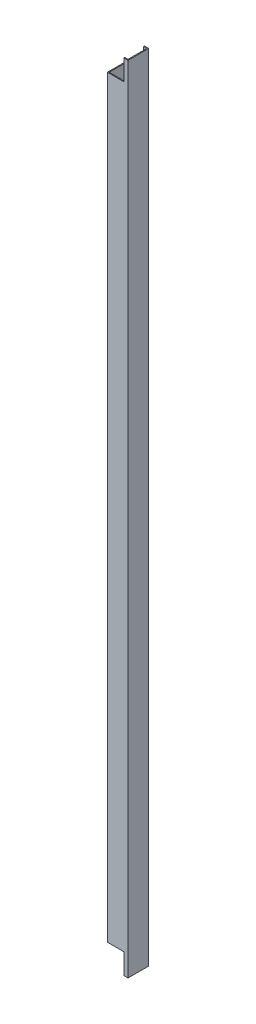
SolidWorks part; units mm, degrees
ref_plane "Front Plane" through (0, 0, 0) normal (0, 0, 1) x (1, 0, 0)
ref_plane "Top Plane" through (0, 0, 0) normal (0, 1, 0) x (1, 0, 0)
ref_plane "Right Plane" through (0, 0, 0) normal (1, 0, 0) x (0, 0, -1)
sketch "Sketch1" plane through (0, 0, 0) normal (0, 1, 0) x (1, 0, 0)
  line L0 (0, 0) -> (0, 50)
  line L1 (0, 50) -> (50, 50)
  line L2 (50, 50) -> (50, 0)
  line L3 (50, 0) -> (0, 0)
  line L4 (2.2, 47.8) -> (47.8, 47.8)
  line L5 (47.8, 47.8) -> (47.8, 2.2)
  line L6 (47.8, 2.2) -> (2.2, 2.2)
  line L7 (2.2, 2.2) -> (2.2, 47.8)
  dimension "D1" = 50
  dimension "D2" = 50
  dimension "D3" = 2.2
extrude "Boss-Extrude1" add sketch "Sketch1" along normal blind 1923
sketch "Sketch2" plane through (0, 0, 0) normal (0, 0, 1) x (1, 0, 0)
  line L0 (0, 0) -> (0, 50)
  line L1 (0, 1923) -> (0, 0) construction
  line L2 (0, 50) -> (40, 50)
  line L3 (40, 50) -> (40, 0)
  line L5 (40, 0) -> (0, 0)
  line L6 (0, 1923) -> (40, 1923)
  line L7 (0, 1923) -> (50, 1923) construction
  line L8 (40, 1923) -> (40, 1873)
  line L9 (40, 1873) -> (0, 1873)
  line L10 (0, 1873) -> (0, 1923)
  dimension "D1" = 50
  dimension "D2" = 40
  dimension "D3" = 50
  dimension "40" = 40
extrude "Cut-Extrude2" cut sketch "Sketch2" against normal blind 50
equation "\"SquareTube_length\"=1923.0"
equation "\"D1@Boss-Extrude1\"=\"SquareTube_length\""
equation "\"SquareTube_inFront1_cutDepth50_R\"=0.5"
equation "\"D1@Sketch2\" = \"SquareTube_inFront5_cutDepth50_R\""
equation "\"SquareTube_inFront1_cutDepth50_L\"=0.5"
equation "\"D3@Sketch2\"= \"SquareTube_inFront5_cutDepth50_L\""
equation "\"CarBeamWidth\"=700.0"
equation "\"MetalSheet_3mm_length\"=5030.0"
equation "\"MetalSheet_3mm_width\"=1923.0"
equation "\"MetalSheet_3mm_FloorCut_L_length\"=1764.0"
equation "\"MetalSheet_3mm_FloorCut_L_disdance\"=1665.0"
equation "\"MetalSheet_3mm_FloorCut_R_length\"=1764.0"
equation "\"MetalSheet_3mm_FloorCut_R_disdance\"=1665.0"
equation "\"indoorHeight\"=1940.0"
equation "\"x\"=66.0"
equation "\"da\"=62.0"
equation "\"SquareTube_wheel_length\"= 750"
equation "\"channelSteel_length\"=5030.0"
equation "\"SquareTube_inFront2_cutDepth50_R\"=0.5"
equation "\"SquareTube_inFront2_cutDepth50_L\"=0.5"
equation "\"SquareTube_inFront3_cutDepth50_R\"=0.5"
equation "\"SquareTube_inFront3_cutDepth50_L\"=0.5"
equation "\"SquareTube_inFront4_cutDepth50_R\"=0.5"
equation "\"SquareTube_inFront4_cutDepth50_L\"=0.5"
equation "\"SquareTube_inFront5_cutDepth50_R\"=50"
equation "\"SquareTube_inFront5_cutDepth50_L\"=50"
equation "\"SquareTube_inFront6_cutDepth50_R\"=50"
equation "\"SquareTube_inFront6_cutDepth50_L\"=50"
equation "\"SquareTube_inFront7_cutDepth50_R\"=50"
equation "\"SquareTube_inFront7_cutDepth50_L\"=50"
equation "\"SquareTube_inFront8_cutDepth50_R\"=50"
equation "\"SquareTube_inFront8_cutDepth50_L\"=50"
equation "\"SquareTube_inFront9_cutDepth50_R\"=50"
equation "\"SquareTube_inFront9_cutDepth50_L\"=50"
equation "\"SquareTube_inFront10_cutDepth50_R\"=50"
equation "\"SquareTube_inFront10_cutDepth50_L\"=50"
equation "\"SquareTube_inBack1_cutDepth50_R\"=50"
equation "\"SquareTube_inBack1_cutDepth50_L\"=50"
equation "\"SquareTube_inBack2_cutDepth50_R\"=50"
equation "\"SquareTube_inBack2_cutDepth50_L\"=50"
equation "\"SquareTube_inBack3_cutDepth50_R\"=50"
equation "\"SquareTube_inBack3_cutDepth50_L\"=50"
equation "\"SquareTube_inBack4_cutDepth50_R\"=50"
equation "\"SquareTube_inBack4_cutDepth50_L\"=50"
equation "\"SquareTube_inBack5_cutDepth50_R\"=50"
equation "\"SquareTube_inBack5_cutDepth50_L\"=50"
equation "\"SquareTube_inBack6_cutDepth50_R\"=0.5"
equation "\"SquareTube_inBack6_cutDepth50_L\"=0.5"
